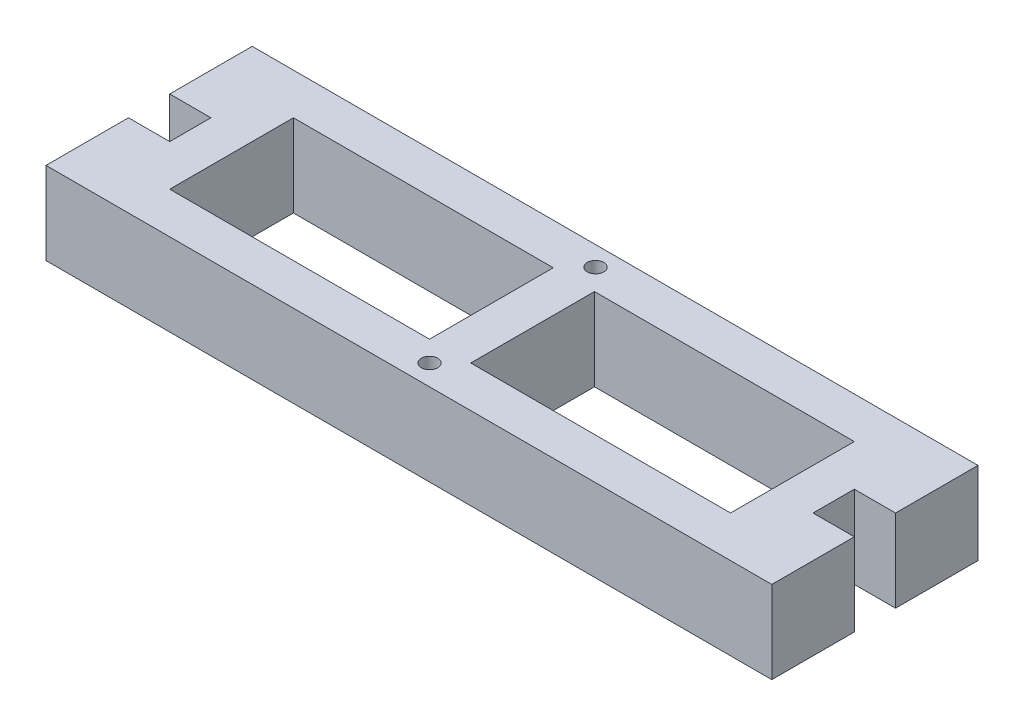
SolidWorks part; units mm, degrees
ref_plane "Front Plane" through (0, 0, 0) normal (0, 0, 1) x (1, 0, 0)
ref_plane "Top Plane" through (0, 0, 0) normal (0, 1, 0) x (1, 0, 0)
ref_plane "Right Plane" through (0, 0, 0) normal (1, 0, 0) x (0, 0, -1)
sketch "Sketch1" plane through (0, 0, 0) normal (0, 1, 0) x (1, 0, 0)
  line L1 (-49, 12.5) -> (49, 12.5)
  line L2 (-49, 12.5) -> (-49, -12.5)
  line L3 (-49, -12.5) -> (49, -12.5)
  line L4 (49, 12.5) -> (49, -12.5)
  line L5 (-49, 12.5) -> (49, -12.5) construction
  line L6 (-49, -12.5) -> (49, 12.5) construction
  point P0 (0, 0)
extrude "Boss-Extrude1" add sketch "Sketch1" along normal blind 10
sketch "Sketch2" plane through (0, 10, 0) normal (0, 1, 0) x (1, 0, 0)
  line L5 (-49, 0) -> (-34, 0)
  line L6 (-49, 12.5) -> (-49, -12.5) construction
  line L7 (34, 7.5) -> (34, -7.5)
  line L16 (-34, -7.5) -> (-34, 7.5)
  line L19 (49, 0) -> (34, 0)
  line L20 (34, -7.5) -> (2.5, -7.5)
  line L25 (49, -12.5) -> (49, 12.5) construction
  line L26 (34, 7.5) -> (2.5, 7.5)
  line L27 (-2.5, 7.5) -> (-34, 7.5)
  line L28 (-2.5, -7.5) -> (-34, -7.5)
  line L29 (2.5, 2.404) -> (2.5, 7.5)
  line L30 (2.5, 2.404) -> (2.5, -7.5)
  line L31 (-2.5, 2.404) -> (-2.5, 7.5)
  line L32 (-2.5, 2.404) -> (-2.5, -7.5)
  line L33 (-18.25, 7.5) -> (-18.25, 12.5)
  line L34 (49, 12.5) -> (-49, 12.5) construction
  point P0 (0, 0)
  point P10 (0, 0)
  point P11 (0, 0)
extrude "Cut-Extrude4" cut sketch "Sketch2" against normal blind 10 contours L32 L31 L27 L16 L28 | L29 L30 L20 L7 L26
sketch "Sketch4" plane through (-49, 0, 0) normal (-1, 0, 0) x (0, 0, 1)
  line L1 (-12.5, 0) -> (12.5, 0)
  line L2 (-12.5, 0) -> (-12.5, 10)
  line L3 (-12.5, 10) -> (12.5, 10)
  line L4 (12.5, 0) -> (12.5, 10)
extrude "Cut-Extrude6" cut sketch "Sketch4" against normal blind 5
sketch "Sketch5" plane through (49, 0, 0) normal (1, 0, 0) x (0, 0, -1)
  line L1 (12.5, 10) -> (-12.5, 10)
  line L2 (12.5, 10) -> (12.5, 0)
  line L3 (12.5, 0) -> (-12.5, 0)
  line L4 (-12.5, 10) -> (-12.5, 0)
extrude "Cut-Extrude7" cut sketch "Sketch5" against normal blind 5
sketch "Sketch6" plane through (44, 0, 0) normal (1, 0, 0) x (0, 0, -1)
  line L1 (12.5, 10) -> (-12.5, 10) construction
  line L2 (-2.5, 10) -> (2.5, 10)
  line L3 (2.5, 10) -> (2.5, 0)
  line L4 (-12.5, 0) -> (12.5, 0) construction
  line L5 (2.5, 0) -> (-2.5, 0)
  line L6 (-2.5, 10) -> (-2.5, 0)
extrude "Cut-Extrude8" cut sketch "Sketch6" against normal blind 5
sketch "Sketch7" plane through (-44, 0, 0) normal (-1, 0, 0) x (0, 0, 1)
  line L1 (-2.5, 0) -> (2.5, 0)
  line L2 (-2.5, 0) -> (-2.5, 10)
  line L3 (-2.5, 10) -> (2.5, 10)
  line L4 (2.5, 0) -> (2.5, 10)
extrude "Cut-Extrude9" cut sketch "Sketch7" against normal blind 5
sketch "Sketch8" plane through (0, 0, 0) normal (0, -1, 0) x (1, 0, 0)
  line L1 (-44, 12.5) -> (44, 12.5) construction
  line L3 (0, 7.5) -> (0, 12.5)
  circle A0 centre (0, 10) radius 1.75
  dimension "D1" = 3.5
extrude "Cut-Extrude10" cut sketch "Sketch8" against normal blind 1.5 contours L3 A0 | L3 A0
sketch "Sketch9" plane through (0, 1.5, 0) normal (0, -1, 0) x (1, 0, 0)
  circle A0 centre (0, 10) radius 1
extrude "Cut-Extrude11" cut sketch "Sketch9" against normal blind 11.5
sketch "Sketch10" plane through (0, 0, 0) normal (0, -1, 0) x (1, 0, 0)
  line L1 (44, -12.5) -> (-44, -12.5) construction
  line L3 (0, -7.5) -> (0, -9.1293)
  line L4 (0, -11.1293) -> (0, -12.5)
  circle A0 centre (0, -10.1293) radius 1
  dimension "D1" = 2
extrude "Cut-Extrude12" cut sketch "Sketch10" against normal blind 19.5 contours A0
sketch "Sketch11" plane through (0, 0, 0) normal (0, -1, 0) x (1, 0, 0)
  circle A0 centre (0, -10.1293) radius 1.75
  dimension "D1" = 3.5
extrude "Cut-Extrude13" cut sketch "Sketch11" against normal blind 1.5
